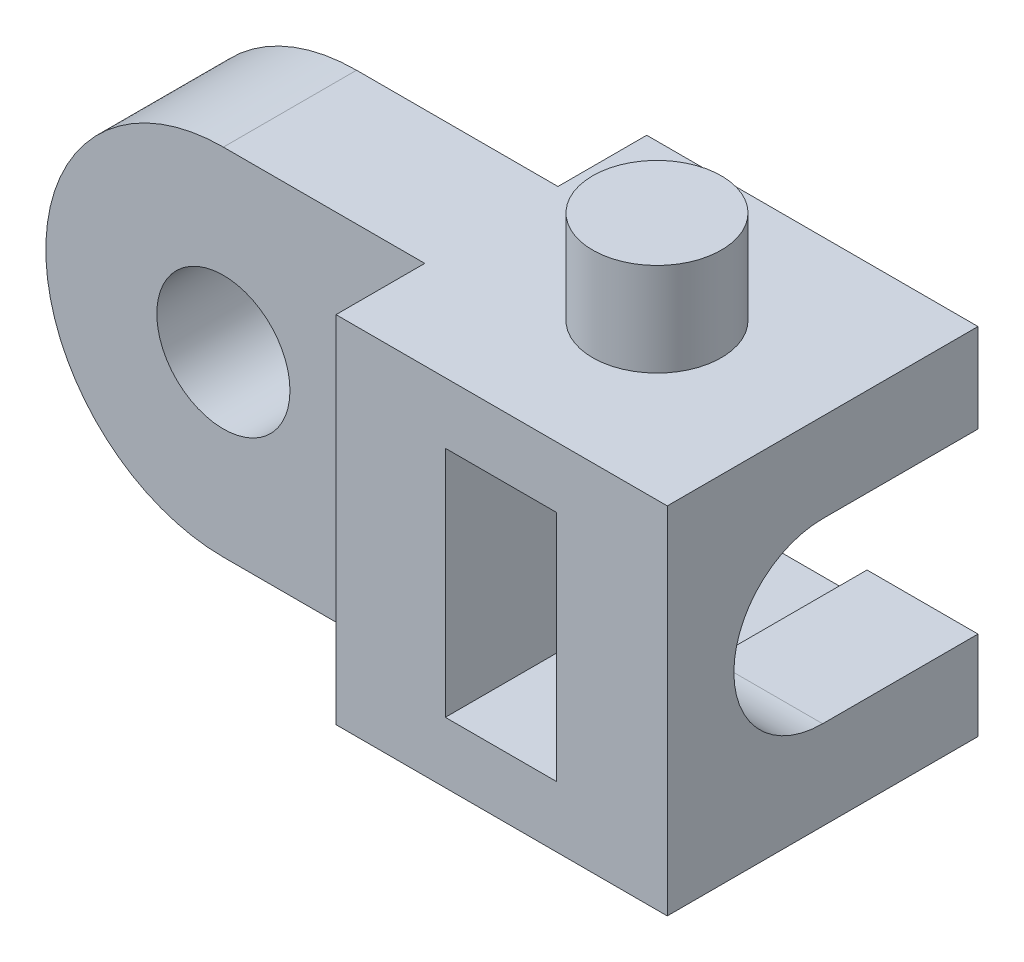
SolidWorks part; units mm, degrees
ref_plane "Спереди" through (0, 0, 0) normal (0, 0, 1) x (1, 0, 0)
ref_plane "Сверху" through (0, 0, 0) normal (0, 1, 0) x (1, 0, 0)
ref_plane "Справа" through (0, 0, 0) normal (1, 0, 0) x (0, 0, -1)
sketch "Sketch1" plane through (0, 0, 0) normal (0, 0, 1) x (1, 0, 0)
  line L0 (0, 0) -> (5.6788, 0) construction
  line L1 (0, 4) -> (12, 4)
  line L2 (0, -4) -> (12, -4)
  line L3 (12, 4) -> (12, -4)
  line L4 (12, -2) -> (12, 2)
  circle A0 centre (0, 0) radius 1.5
  circle A1 centre (0, 0) radius 4
  point P12 (12, 0)
  dimension "D1" = 3
  dimension "D2" = 8
  dimension "D3" = 4
  dimension "D4" = 4
  dimension "D5" = 12
  dimension "D6" = 4
extrude "Boss-Extrude1" add sketch "Sketch1" along normal mid plane 3
sketch "Sketch5" plane through (0, 0, 0) normal (0, 0, 1) x (1, 0, 0)
  line L0 (0, 4) -> (12, 4) construction
  line L1 (12, -4) -> (4.5369, -4)
  line L2 (12, -4) -> (12, 4)
  line L3 (12, 4) -> (4.5369, 4)
  line L4 (4.5369, -4) -> (4.5369, 4)
extrude "Boss-Extrude2" add sketch "Sketch5" along normal mid plane 7
sketch "Sketch2" plane through (0, 0, 1.5) normal (0, 0, 1) x (1, 0, 0)
  line L0 (12, 0) -> (8.25, 0) construction
  line L1 (12, 4) -> (12, -4) construction
  line L3 (7, 2.625) -> (9.5, 2.625)
  line L4 (7, 2.625) -> (7, -2.625)
  line L5 (7, -2.625) -> (9.5, -2.625)
  line L6 (9.5, 2.625) -> (9.5, -2.625)
  line L7 (7, 2.625) -> (9.5, -2.625) construction
  line L8 (7, -2.625) -> (9.5, 2.625) construction
  dimension "D1" = 2.5
  dimension "D2" = 5.25
  dimension "D3" = 2.5
extrude "Cut-Extrude1" cut sketch "Sketch2" against normal blind 6 and the other way blind 7
sketch "Sketch3" plane through (12, 0, 0) normal (1, 0, 0) x (0, 0, -1)
  circle A0 centre (0, 0) radius 2
  dimension "D1" = 4
extrude "Cut-Extrude2" cut sketch "Sketch3" against normal blind 3
sketch "Sketch6" plane through (0, 0, -3.5) normal (0, 0, -1) x (-1, 0, 0)
  line L0 (0, 0) -> (-12, 0) construction
  line L1 (-12, -4) -> (-12, 4) construction
  line L2 (-9.5, 2.625) -> (-9.5, -2.625) construction
  line L3 (-14.5, -2) -> (-9.5, -2)
  line L4 (-14.5, -2) -> (-14.5, 2)
  line L5 (-14.5, 2) -> (-9.5, 2)
  line L6 (-9.5, -2) -> (-9.5, 2)
  line L7 (-14.5, -2) -> (-9.5, 2) construction
  line L8 (-14.5, 2) -> (-9.5, -2) construction
  dimension "D1" = 4
extrude "Cut-Extrude3" cut sketch "Sketch6" against normal blind 3.5
sketch "Sketch7" plane through (0, 4, 0) normal (0, 1, 0) x (1, 0, 0)
  line L0 (12, 0) -> (4.4927, 0) construction
  line L1 (12, -3.5) -> (12, 3.5) construction
  line L2 (12, -1.5) -> (4.5369, -1.5) construction
  line L3 (0, -1.5) -> (4.5369, -1.5) construction
  line L4 (4.5369, -3.5) -> (4.5369, -1.5) construction
  line L5 (8.2685, -1.5) -> (8.2685, 1.5) construction
  circle A1 centre (8.2685, 0) radius 1.45
  dimension "D1" = 2.9
extrude "Boss-Extrude3" add sketch "Sketch7" along normal blind 2.1
sketch "Sketch8" plane through (0, 6.1, 0) normal (0, 1, 0) x (1, 0, 0)
  circle A0 centre (8.2464, 0) radius 3.5
extrude "Boss-Extrude4" [suppressed] add sketch "Sketch8" along normal blind 2
